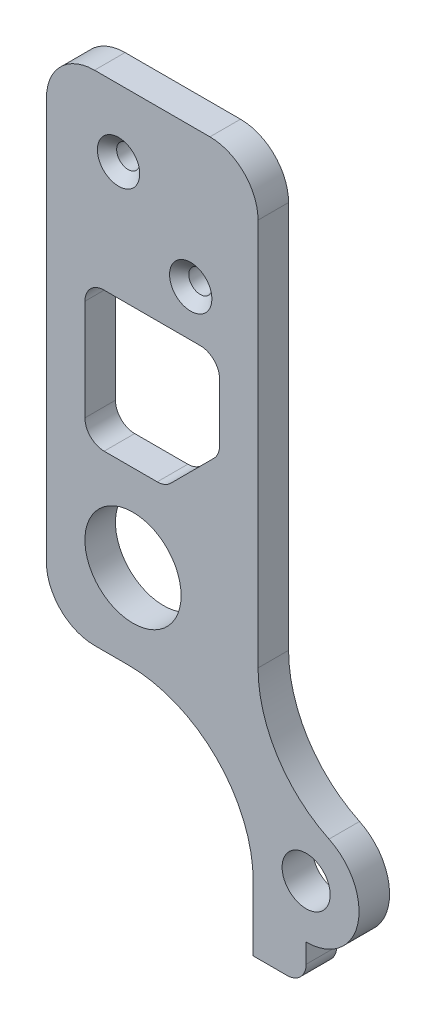
SolidWorks part; units mm, degrees
material "6061-T4 (SS)"
ref_plane "Front" through (0, 0, 0) normal (0, 0, 1) x (1, 0, 0)
ref_plane "Top" through (0, 0, 0) normal (0, 1, 0) x (1, 0, 0)
ref_plane "Right" through (0, 0, 0) normal (1, 0, 0) x (0, 0, -1)
sketch "Sketch1" plane through (0, 0, 0) normal (0, 0, 1) x (1, 0, 0)
  line L8 (0, -5.5) -> (-7, -5.5)
  line L9 (-7, -5.5) -> (-7, -9)
  line L57 (-7, -9) -> (-12, -9)
  line L58 (-12, -9) -> (-12, -2.5)
  line L60 (-27, 4.4946) -> (-27, 62)
  line L61 (-27, 62) -> (-5, 62)
  line L62 (-5, 62) -> (-5, 32.1963)
  line L63 (-5, 32.1963) -> (-9, 28.1963)
  line L64 (-9, 28.1963) -> (-9, 10.2653)
  line L65 (-9, 10.2653) -> (2.3244, 4.9847)
  line L66 (-12, -2.5) -> (-27, 4.4946)
  circle A8 centre (0, 0) radius 2.5
  arc A9 (0, -5.5) -> (2.3244, 4.9847) centre (0, 0) ccw
  circle A10 centre (0, 0) radius 5.5 construction
  circle A11 centre (-18, 19.2) radius 5
  circle A12 centre (-18, 19.2) radius 9 construction
  circle A13 centre (-16, 35.6791) radius 5 construction
  circle A14 centre (-16, 35.6791) radius 8 construction
  point P47 (-16, 62)
  dimension "D7" = 2.5
  dimension "D22" = 5
  dimension "D27" = 10
  dimension "D33" = 10
  dimension "D37" = 16
  dimension "D1" = 28.1963
  dimension "D24" = 9
  dimension "D25" = 5
  dimension "D26" = 7
  dimension "D28" = 18
  dimension "D30" = 115
  dimension "D31" = 135
  dimension "D32" = 19.2
  dimension "D34" = 16.6
  dimension "D35" = 16
  dimension "D36" = 62
  dimension "D23" = 3
  dimension "D29" = 4
extrude "Boss-Extrude1" add sketch "Sketch1" along normal blind 3.175
sketch "L-Bar_Outline" plane through (0, 0, 3.175) normal (0, 0, -1) x (-1, 0, 0)
  line L0 (10, 57) -> (22, 57) construction
  line L1 (22, 57) -> (22, 53) construction
  line L2 (22, 53) -> (14, 53) construction
  line L3 (14, 53) -> (14, 45) construction
  line L4 (14, 45) -> (10, 45) construction
  line L5 (10, 45) -> (10, 57) construction
  line L6 (27, 4.4946) -> (27, 62) construction
  line L7 (27, 62) -> (5, 62) construction
  line L8 (12, 47.5) -> (12, 55) construction
  line L9 (12, 55) -> (19.5, 55) construction
  line L10 (10, 47.5) -> (14, 47.5) construction
  line L11 (19.5, 57) -> (19.5, 53) construction
  dimension "D1" = 12
  dimension "D2" = 4
  dimension "D3" = 4
  dimension "D4" = 12
  dimension "D5" = 5
  dimension "D6" = 5
  dimension "D7" = 2.5
  dimension "D8" = 2.5
hole_wizard "CSK for M2 Flat Head Machine Screw3" positions "Sketch9" profile "Sketch10" countersink size "M2" standard "ANSI Metric" end condition up to next
sketch "Sketch9" plane through (0, 0, 3.175) normal (0, 0, 1) x (1, 0, 0)
  point P0 (-19.5, 55)
  point P3 (-12, 47.5)
sketch "Sketch10" plane through (-19.5, 55, 3.175) normal (1, 0, 0) x (0, -1, 0)
  line L0 (0, 0) -> (0, 3.175)
  line L1 (0, 3.175) -> (1.2, 3.175)
  line L2 (1.2, 3.175) -> (1.2, 1)
  line L3 (1.2, 1) -> (2.2, 0)
  line L5 (2.2, 0) -> (0, 0)
  line L6 (-1.2, 1) -> (-2.2, 0) construction
  line L11 (0, -6.35) -> (0, 107.95) construction
  dimension "Thru Hole Dia." = 2.4
  dimension "Thru Hole Depth" = 3.175
  dimension "Near C'Sink Dia." = 4.4
  dimension "Near C'Sink Angle" = 90
sketch "Sketch11" plane through (0, 0, 3.175) normal (0, 0, 1) x (1, 0, 0)
  line L1 (-9, 28.1963) -> (-13, 28.1963) construction
  line L9 (-27, 4.4946) -> (-27, 62) construction
  line L26 (-23, 28.1963) -> (-23, 42.6963)
  line L48 (-23, 42.6963) -> (-9, 42.6963)
  line L49 (-23, 28.1963) -> (-14.65, 28.1963)
  line L51 (-9, 33.8532) -> (-14.65, 28.1963)
  line L52 (-13, 29.8532) -> (-13, 10.2653)
  line L53 (-9, 33.8532) -> (-13, 29.8532)
  line L54 (-9, 62) -> (-9, 33.8532)
  line L57 (-9, 42.6963) -> (-9, 33.8532)
  line L58 (-14.65, 28.1963) -> (-27, 28.1963) construction
  point P0 (-16, 35.6791)
  dimension "D1" = 14.5
  dimension "D2" = 4
  dimension "D3" = 8.35
  dimension "D8" = 4
extrude "Cut-Extrude2" cut sketch "Sketch11" against normal through all contours L26 L48 L57 L51 L49
fillet "5mm_Fillet" radius 5 7 edges at (-9, 10.2653, 1.5875) (-9, 28.1963, 1.5875) (-5, 32.1963, 1.5875) (-12, -2.5, 1.5875) (-27, 4.4946, 1.5875) (-27, 62, 1.5875) (-5, 62, 1.5875)
fillet "2mm_Fillet" radius 2 5 edges at (-9, 42.6963, 1.5875) (-23, 28.1963, 1.5875) (-9, 33.8532, 1.5875) (-14.65, 28.1963, 1.5875) (-23, 42.6963, 1.5875)
fillet "1mm_Fillet" radius 1 2 edges at (-7, -9, 1.5875) (-7, -5.5, 1.5875)
sketch "Sketch12" plane through (0, 0, 3.175) normal (0, 0, 1) x (1, 0, 0)
  line L0 (-27, 10.1996) -> (-27, -4.6904)
  line L1 (-27, 7.68) -> (-27, 57) construction
  line L2 (-27, -4.6904) -> (-12.1, -4.6904)
  line L3 (-12.1, -4.6904) -> (-12.1, 5.1996)
  line L4 (-17.1, 10.1996) -> (-27, 10.1996)
  arc A0 (-12.1, 5.1996) -> (-17.1, 10.1996) centre (-17.1, 5.1996) ccw
  arc A3 (-12, -5.6854) -> (-14.8869, -1.1538) centre (-17, -5.6854) ccw construction
  dimension "D1" = 5
  dimension "D2" = 14.89
  dimension "D3" = 14.9
extrude "Cut-Extrude3" cut sketch "Sketch12" against normal through all
fillet "Fillet1" radius 5 1 edges at (-27, 10.1996, 1.5875)
sketch "Sketch13" plane through (0, 0, 3.175) normal (0, 0, 1) x (1, 0, 0)
  line L0 (-5, 34.2674) -> (-5, 8.4001)
  line L12 (-27, 57) -> (-27, 15.1996)
  line L13 (-22, 10.1996) -> (-17.1, 10.1996)
  line L14 (-12.1, 5.1996) -> (-12.1, -4.6904)
  line L15 (-12, -5.6854) -> (-12, -9)
  line L16 (-12, -9) -> (-8, -9)
  line L17 (-7, -8) -> (-7, -6.5)
  line L18 (-6, -5.5) -> (0, -5.5)
  line L19 (2.3244, 4.9847) -> (-6.1131, 8.9192)
  line L20 (-9, 13.4507) -> (-9, 26.1253)
  line L21 (-7.5355, 29.6608) -> (-6.4645, 30.7319)
  line L22 (-5, 34.2674) -> (-5, 57)
  line L23 (-10, 62) -> (-22, 62)
  line L24 (-27, 57) -> (-27, 15.1996)
  line L25 (-22, 10.1996) -> (-17.1, 10.1996)
  line L26 (-12.1, 5.1996) -> (-12.1, -4.6904)
  line L27 (-12, -5.6854) -> (-12, -9)
  line L28 (-12, -9) -> (-8, -9)
  line L29 (-7, -8) -> (-7, -6.5)
  line L30 (-6, -5.5) -> (0, -5.5)
  line L31 (-5, 8.4001) -> (-6.1131, 8.9192)
  line L32 (-9, 13.4507) -> (-9, 26.1253)
  line L33 (-7.5355, 29.6608) -> (-6.4645, 30.7319)
  line L35 (-10, 62) -> (-22, 62)
  circle A0 centre (0, 0) radius 5.5
  arc A11 (-27, 15.1996) -> (-22, 10.1996) centre (-22, 15.1996) ccw
  arc A12 (-12.1, 5.1996) -> (-17.1, 10.1996) centre (-17.1, 5.1996) ccw
  arc A13 (-12, -5.6854) -> (-12.1, -4.6904) centre (-17, -5.6854) ccw
  arc A14 (-8, -9) -> (-7, -8) centre (-8, -8) ccw
  arc A15 (-6, -5.5) -> (-7, -6.5) centre (-6, -6.5) ccw
  arc A16 (0, -5.5) -> (2.3244, 4.9847) centre (0, 0) ccw
  arc A17 (-9, 13.4507) -> (-6.1131, 8.9192) centre (-4, 13.4507) ccw
  arc A18 (-7.5355, 29.6608) -> (-9, 26.1253) centre (-4, 26.1253) ccw
  arc A19 (-6.4645, 30.7319) -> (-5, 34.2674) centre (-10, 34.2674) ccw
  arc A20 (-5, 57) -> (-10, 62) centre (-10, 57) ccw
  arc A21 (-22, 62) -> (-27, 57) centre (-22, 57) ccw
  arc A22 (-27, 15.1996) -> (-22, 10.1996) centre (-22, 15.1996) ccw
  arc A23 (-12.1, 5.1996) -> (-17.1, 10.1996) centre (-17.1, 5.1996) ccw
  arc A24 (-12, -5.6854) -> (-12.1, -4.6904) centre (-17, -5.6854) ccw
  arc A25 (-8, -9) -> (-7, -8) centre (-8, -8) ccw
  arc A26 (-6, -5.5) -> (-7, -6.5) centre (-6, -6.5) ccw
  arc A27 (0, -5.5) -> (2.3244, 4.9847) centre (0, 0) ccw
  arc A28 (-9, 13.4507) -> (-6.1131, 8.9192) centre (-4, 13.4507) ccw
  arc A29 (-7.5355, 29.6608) -> (-9, 26.1253) centre (-4, 26.1253) ccw
  arc A30 (-6.4645, 30.7319) -> (-5, 34.2674) centre (-10, 34.2674) ccw
  arc A31 (-5, 57) -> (-10, 62) centre (-10, 57) ccw
  arc A32 (-22, 62) -> (-27, 57) centre (-22, 57) ccw
  dimension "D1" = 0
extrude "Boss-Extrude2" add sketch "Sketch13" against normal up to surface (3.175 mm away) contours L32 A29 L33 A30 L0 L31 A28 up to face at (-15.6343, 35.0321, 0)
sketch "Sketch14" plane through (0, 0, 3.175) normal (0, 0, 1) x (1, 0, 0)
  line L0 (-5.5, 0) -> (-5.5, -9.5)
  line L1 (0, -5.5) -> (0, -9.5)
  line L2 (0, -9.5) -> (-5.5, -9.5)
  line L11 (-5, 8.4001) -> (-5, 57)
  line L12 (-10, 62) -> (-22, 62)
  line L13 (-27, 57) -> (-27, 15.1996)
  line L14 (-22, 10.1996) -> (-17.1, 10.1996)
  line L15 (-12.1, 5.1996) -> (-12.1, -4.6904)
  line L16 (-12, -5.6854) -> (-12, -9)
  line L17 (-12, -9) -> (-8, -9)
  line L18 (-7, -8) -> (-7, -6.5)
  line L19 (-6, -5.5) -> (0, -5.5)
  line L21 (-5, 8.4001) -> (-5, 57)
  line L22 (-10, 62) -> (-22, 62)
  line L23 (-27, 57) -> (-27, 15.1996)
  line L24 (-22, 10.1996) -> (-17.1, 10.1996)
  line L25 (-12.1, 5.1996) -> (-12.1, -4.6904)
  line L26 (-12, -5.6854) -> (-12, -9)
  line L27 (-12, -9) -> (-8, -9)
  line L28 (-7, -8) -> (-7, -6.5)
  line L29 (-6, -5.5) -> (0, -5.5)
  line L32 (2.3244, 4.9847) -> (-5, 8.4001)
  line L33 (2.3244, 4.9847) -> (-5, 8.4001)
  arc A1 (0, -5.5) -> (-5.5, 0) centre (0, 0) ccw
  arc A2 (-5.5, 0) -> (0, -5.5) centre (0, 0) ccw
  arc A10 (-5, 57) -> (-10, 62) centre (-10, 57) ccw
  arc A11 (-22, 62) -> (-27, 57) centre (-22, 57) ccw
  arc A12 (-27, 15.1996) -> (-22, 10.1996) centre (-22, 15.1996) ccw
  arc A13 (-12.1, 5.1996) -> (-17.1, 10.1996) centre (-17.1, 5.1996) ccw
  arc A14 (-12, -5.6854) -> (-12.1, -4.6904) centre (-17, -5.6854) ccw
  arc A15 (-8, -9) -> (-7, -8) centre (-8, -8) ccw
  arc A16 (-6, -5.5) -> (-7, -6.5) centre (-6, -6.5) ccw
  arc A17 (0, -5.5) -> (2.3244, 4.9847) centre (0, 0) ccw
  arc A19 (-5, 57) -> (-10, 62) centre (-10, 57) ccw
  arc A20 (-22, 62) -> (-27, 57) centre (-22, 57) ccw
  arc A21 (-27, 15.1996) -> (-22, 10.1996) centre (-22, 15.1996) ccw
  arc A22 (-12.1, 5.1996) -> (-17.1, 10.1996) centre (-17.1, 5.1996) ccw
  arc A23 (-12, -5.6854) -> (-12.1, -4.6904) centre (-17, -5.6854) ccw
  arc A24 (-8, -9) -> (-7, -8) centre (-8, -8) ccw
  arc A25 (-6, -5.5) -> (-7, -6.5) centre (-6, -6.5) ccw
  arc A26 (0, -5.5) -> (2.3244, 4.9847) centre (0, 0) ccw
  line M40 (-6, -5.5) -> (0, -5.5)
  dimension "D2" = 4
  dimension "D1" = 0
extrude "Boss-Extrude3" add sketch "Sketch14" against normal up to surface (3.175 mm away) contours L2 L1 L0 M40 | A2 L0 M40 up to face at (-11.3746, 13.3027, 0)
fillet "Fillet3" radius 2 1 edges at (0, -9.5, 1.5875)
sketch "Sketch15" plane through (0, 0, 3.175) normal (0, 0, 1) x (1, 0, 0)
  line L0 (-22, 10.1996) -> (-5.5, 10.1996)
  line L1 (-5.5, 10.1996) -> (-5.5, -5.5)
  line L2 (-22, 10.1996) -> (-22, -5.5)
  line L3 (-22, -5.5) -> (-5.5, -5.5)
  line L13 (-5.5, -9.5) -> (-2, -9.5)
  line L14 (0, -7.5) -> (0, -5.5)
  line L16 (-5, 8.4001) -> (-5, 57)
  line L17 (-10, 62) -> (-22, 62)
  line L18 (-27, 57) -> (-27, 15.1996)
  line L19 (-22, 10.1996) -> (-17.1, 10.1996)
  line L20 (-12.1, 5.1996) -> (-12.1, -4.6904)
  line L21 (-12, -5.6854) -> (-12, -9)
  line L22 (-12, -9) -> (-8, -9)
  line L23 (-7, -8) -> (-7, -6.5)
  line L25 (-5.5, -5.5) -> (-5.5, -9.5)
  line L26 (-5.5, -9.5) -> (-2, -9.5)
  line L27 (0, -7.5) -> (0, -5.5)
  line L29 (-5, 8.4001) -> (-5, 57)
  line L30 (-10, 62) -> (-22, 62)
  line L31 (-27, 57) -> (-27, 15.1996)
  line L32 (-22, 10.1996) -> (-17.1, 10.1996)
  line L33 (-12.1, 5.1996) -> (-12.1, -4.6904)
  line L34 (-12, -5.6854) -> (-12, -9)
  line L35 (-12, -9) -> (-8, -9)
  line L36 (-7, -8) -> (-7, -6.5)
  line L38 (-5.5, -5.5) -> (-5.5, -9.5)
  line L41 (-6, -5.5) -> (-5.5, -5.5)
  line L42 (2.3244, 4.9847) -> (-5, 8.4001)
  line L43 (2.3244, 4.9847) -> (-5, 8.4001)
  line L44 (-6, -5.5) -> (-5.5, -5.5)
  arc A10 (-2, -9.5) -> (0, -7.5) centre (-2, -7.5) ccw
  arc A11 (0, -5.5) -> (2.3244, 4.9847) centre (0, 0) ccw
  arc A13 (-5, 57) -> (-10, 62) centre (-10, 57) ccw
  arc A14 (-22, 62) -> (-27, 57) centre (-22, 57) ccw
  arc A15 (-27, 15.1996) -> (-22, 10.1996) centre (-22, 15.1996) ccw
  arc A16 (-12.1, 5.1996) -> (-17.1, 10.1996) centre (-17.1, 5.1996) ccw
  arc A17 (-12, -5.6854) -> (-12.1, -4.6904) centre (-17, -5.6854) ccw
  arc A18 (-8, -9) -> (-7, -8) centre (-8, -8) ccw
  arc A19 (-6, -5.5) -> (-7, -6.5) centre (-6, -6.5) ccw
  arc A20 (-2, -9.5) -> (0, -7.5) centre (-2, -7.5) ccw
  arc A21 (0, -5.5) -> (2.3244, 4.9847) centre (0, 0) ccw
  arc A23 (-5, 57) -> (-10, 62) centre (-10, 57) ccw
  arc A24 (-22, 62) -> (-27, 57) centre (-22, 57) ccw
  arc A25 (-27, 15.1996) -> (-22, 10.1996) centre (-22, 15.1996) ccw
  arc A26 (-12.1, 5.1996) -> (-17.1, 10.1996) centre (-17.1, 5.1996) ccw
  arc A27 (-12, -5.6854) -> (-12.1, -4.6904) centre (-17, -5.6854) ccw
  arc A28 (-8, -9) -> (-7, -8) centre (-8, -8) ccw
  arc A29 (-6, -5.5) -> (-7, -6.5) centre (-6, -6.5) ccw
  arc M37 (-17.1, 10.1996) -> (-12.1, 5.1996) centre (-17.1, 5.1996) cw
  line M38 (-12.1, 5.1996) -> (-12.1, -4.6904)
  arc M39 (-12.1, -4.6904) -> (-12, -5.6854) centre (-17, -5.6854) cw
  line M45 (-6, -5.5) -> (-5.5, -5.5)
  dimension "D1" = 0
extrude "Cut-Extrude6" cut sketch "Sketch15" against normal blind 10 and the other way through all contours L3 L1 L0 M39 M45 M37 M38
fillet "Fillet6" radius 13 1 edges at (-5.5, 10.1996, 1.5875)
fillet "Fillet7" radius 13 1 edges at (-5, 8.4001, 1.5875)
